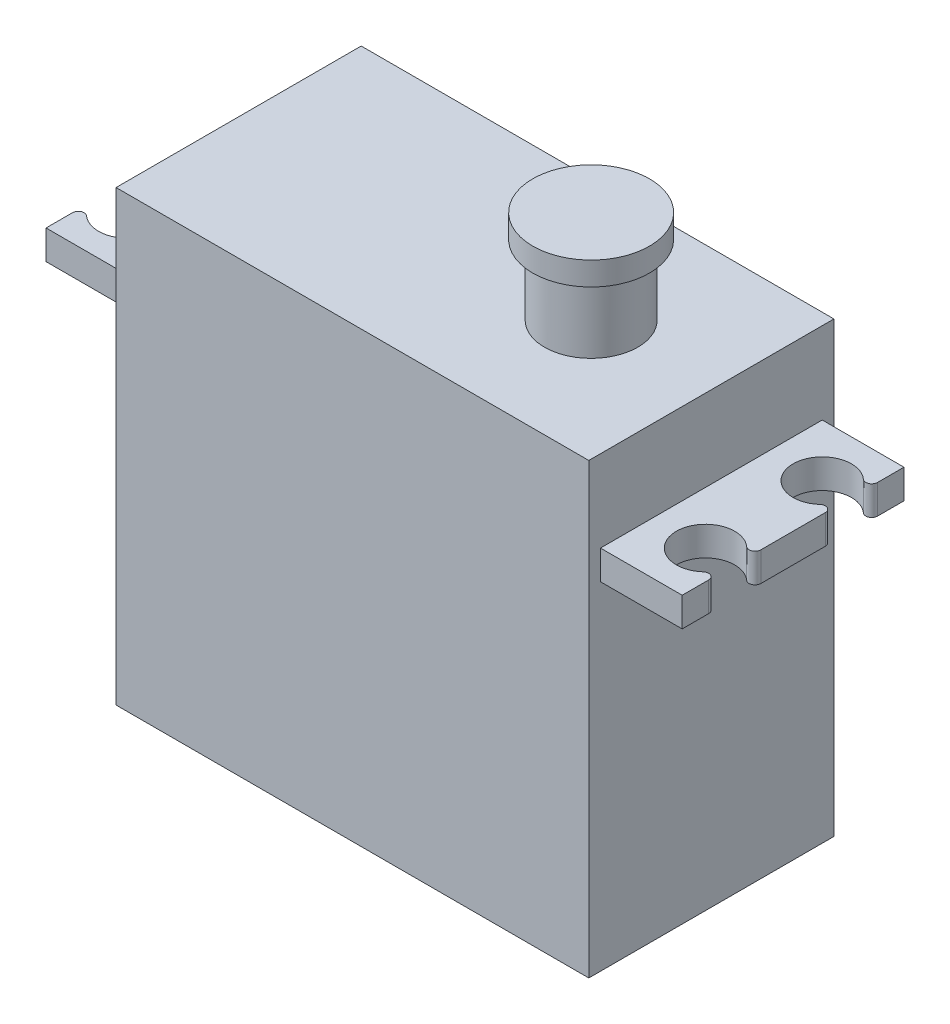
SolidWorks part; units mm, degrees
material "AISI 1015 Steel, Cold Drawn (SS)"
ref_plane "Front Plane" through (0, 0, 0) normal (0, 0, 1) x (1, 0, 0)
ref_plane "Top Plane" through (0, 0, 0) normal (0, 1, 0) x (1, 0, 0)
ref_plane "Right Plane" through (0, 0, 0) normal (1, 0, 0) x (0, 0, -1)
sketch "Sketch1" plane through (0, 0, 0) normal (0, 1, 0) x (1, 0, 0)
  line L0 (0, 98.4413) -> (0, -50.6259) construction
  line L1 (-20.25, -10.5) -> (20.25, -10.5)
  line L2 (-20.25, -10.5) -> (-20.25, 10.5)
  line L3 (-20.25, 10.5) -> (20.25, 10.5)
  line L4 (20.25, -10.5) -> (20.25, 10.5)
  line L5 (-20.25, -10.5) -> (20.25, 10.5) construction
  line L6 (-20.25, 10.5) -> (20.25, -10.5) construction
  line L7 (-67.6585, 0) -> (91.571, 0) construction
  point P0 (0, 0)
  dimension "D1" = 40.5
  dimension "D2" = 21
extrude "Boss-Extrude1" add sketch "Sketch1" along normal blind 38.4
sketch "Sketch2" plane through (0, 38.4, 0) normal (0, 1, 0) x (1, 0, 0)
  line L0 (-25.3405, 0) -> (25.583, 0) construction
  line L1 (20.25, -10.5) -> (20.25, 10.5) construction
  circle A0 centre (9.95, 0) radius 4
  dimension "D2" = 8
  dimension "D1" = 10.3
extrude "Boss-Extrude2" add sketch "Sketch2" along normal blind 6
sketch "Sketch3" plane through (0, 44.4, 0) normal (0, 1, 0) x (1, 0, 0)
  circle A0 centre (9.95, 0) radius 4
  circle A1 centre (9.95, 0) radius 5
  circle M1 centre (9.95, 0) radius 4
  dimension "D1" = 10
extrude "Boss-Extrude3" add sketch "Sketch3" along normal blind 2 separate body contours M1 | A1 M1
sketch "Sketch6" plane through (0, 44.4, 0) normal (0, -1, 0) x (1, 0, 0)
  line L0 (0, 10.5) -> (0, -10.5) construction
  line L1 (27.25, 0) -> (-27.25, 0) construction
  line L2 (9.95, 9.5) -> (9.95, -9.5) construction
  line L3 (20.25, 10.5) -> (20.25, -10.5) construction
  line L4 (-27.25, -7.2361) -> (-27.25, -9.5)
  line L5 (27.25, 9.5) -> (-27.25, 9.5)
  line L6 (27.25, 9.5) -> (27.25, 7.2361)
  line L7 (27.25, -9.5) -> (-27.25, -9.5)
  line L8 (-27.25, 9.5) -> (-27.25, 7.2361)
  line L9 (27.25, 9.5) -> (-27.25, -9.5) construction
  line L10 (27.25, -9.5) -> (-27.25, 9.5) construction
  line L11 (-27.25, 2.7639) -> (-27.25, -2.7639)
  line L12 (27.25, 2.7639) -> (27.25, -2.7639)
  line L13 (-20.25, 10.5) -> (20.25, 10.5) construction
  line L14 (20.25, -10.5) -> (-20.25, -10.5) construction
  line L17 (27.25, -7.2361) -> (27.25, -9.5)
  arc A0 (26.4167, 6.8634) -> (26.4167, 3.1366) centre (24.75, 5) ccw
  arc A1 (26.4167, 6.8634) -> (27.25, 7.2361) centre (26.75, 7.2361) ccw
  arc A2 (27.25, 2.7639) -> (26.4167, 3.1366) centre (26.75, 2.7639) ccw
  arc A3 (27.25, -2.7639) -> (26.4167, -3.1366) centre (26.75, -2.7639) cw
  arc A4 (26.4167, -6.8634) -> (27.25, -7.2361) centre (26.75, -7.2361) cw
  arc A5 (26.4167, -6.8634) -> (26.4167, -3.1366) centre (24.75, -5) cw
  arc A6 (-27.25, 2.7639) -> (-26.4167, 3.1366) centre (-26.75, 2.7639) cw
  arc A7 (-26.4167, 6.8634) -> (-27.25, 7.2361) centre (-26.75, 7.2361) cw
  arc A8 (-26.4167, 6.8634) -> (-26.4167, 3.1366) centre (-24.75, 5) cw
  arc A9 (-26.4167, -6.8634) -> (-26.4167, -3.1366) centre (-24.75, -5) ccw
  arc A10 (-26.4167, -6.8634) -> (-27.25, -7.2361) centre (-26.75, -7.2361) ccw
  arc A11 (-27.25, -2.7639) -> (-26.4167, -3.1366) centre (-26.75, -2.7639) ccw
  point P9 (0, 0)
  dimension "D3" = 5
  dimension "D7" = 0.5
  dimension "D1" = 10.3
  dimension "D2" = 19
  dimension "D4" = 14.8
  dimension "D5" = 5
  dimension "D6" = 54.5
extrude "Boss-Extrude5" add sketch "Sketch6" against normal blind 2.5 from offset 15.5
